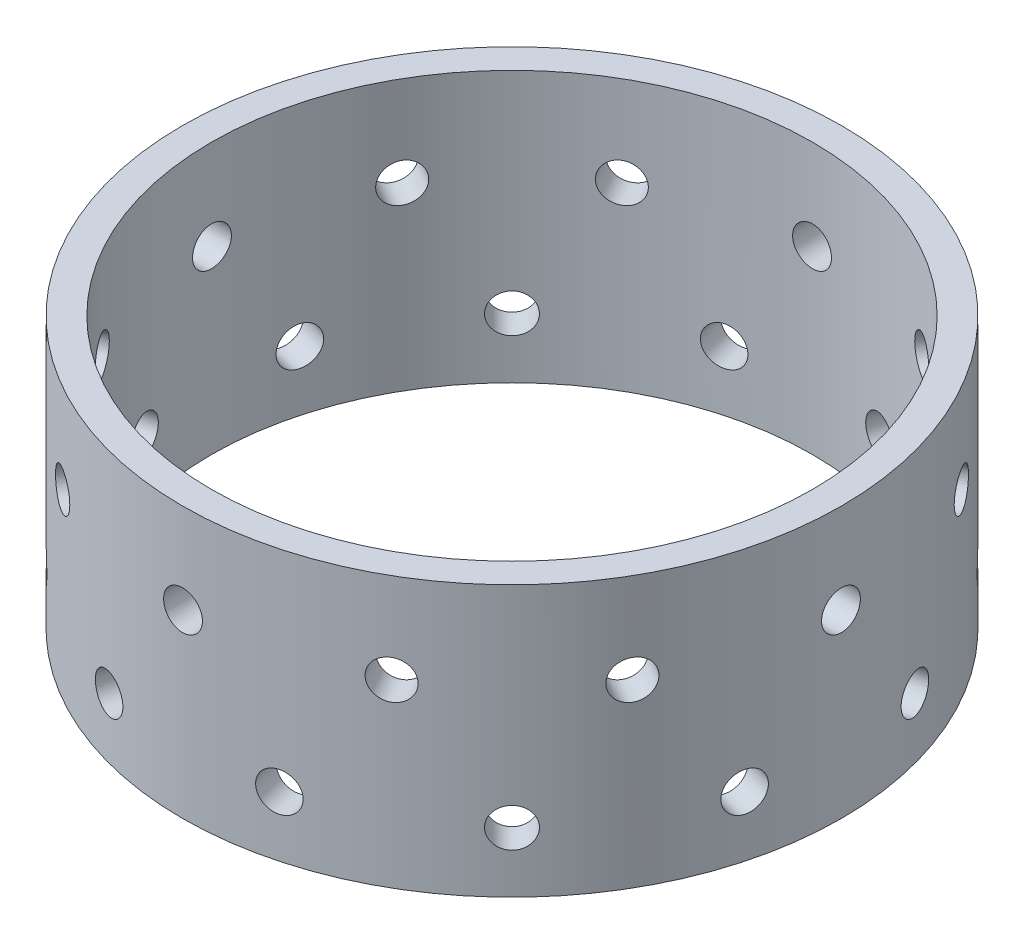
SolidWorks part; units mm, degrees
ref_plane "Front Plane" through (0, 0, 0) normal (0, 0, 1) x (1, 0, 0)
ref_plane "Top Plane" through (0, 0, 0) normal (0, 1, 0) x (1, 0, 0)
ref_plane "Right Plane" through (0, 0, 0) normal (1, 0, 0) x (0, 0, -1)
sketch "Sketch1" plane through (0, 0, 0) normal (0, 1, 0) x (1, 0, 0)
  circle A0 centre (0, 0) radius 69.596
  circle A1 centre (0, 0) radius 63.5
  dimension "D1" = 139.192
  dimension "D2" = 127
extrude "Boss-Extrude1" add sketch "Sketch1" along normal blind 57.15
ref_plane "Plane1" through (0, 0, 69.596) normal (0, 0, 1) x (1, 0, 0)
sketch "Sketch2" plane through (0, 0, 69.596) normal (0, 0, 1) x (1, 0, 0)
  line L0 (69.596, 57.15) -> (-69.596, 57.15) construction
  circle A0 centre (0, 38.1) radius 4.1021
  dimension "D1" = 8.2042
  dimension "D2" = 19.05
extrude "Cut-Extrude1" cut sketch "Sketch2" against normal up to next
pattern_circular "CirPattern1" count 12 over 360 about axis through (0, 57.15, 0) along (0, -1, 0) of "Cut-Extrude1"
ref_plane "Plane2" through (18.0128, 0, -67.2246) normal (0.2588, 0, -0.9659) x (0, -1, 0)
sketch "Sketch3" plane through (18.0128, 0, -67.2246) normal (0.2588, 0, -0.9659) x (0, -1, 0)
  line L0 (-57.15, 69.596) -> (-57.15, -69.596) construction
  circle A0 centre (-12.7, 0) radius 4.1021
  dimension "D1" = 8.2042
  dimension "D2" = 44.45
extrude "Cut-Extrude2" cut sketch "Sketch3" against normal up to next
pattern_circular "CirPattern2" count 12 over 360 about axis through (0, 57.15, 0) along (0, -1, 0) of "Cut-Extrude2"
